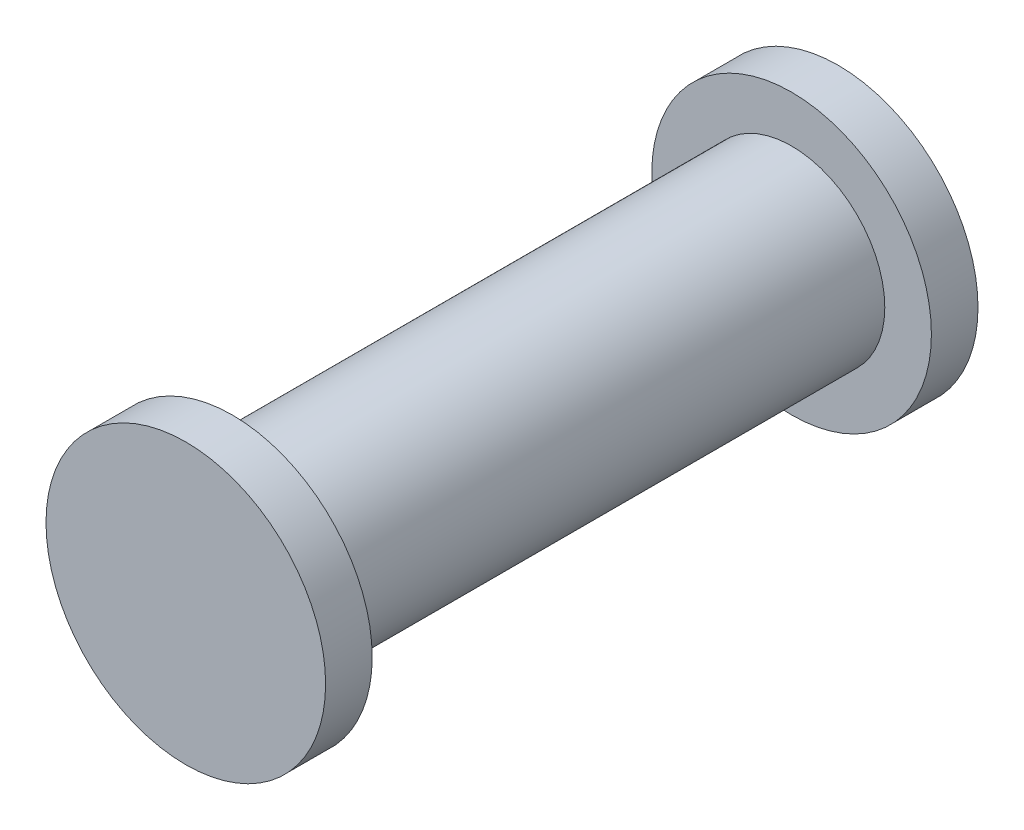
SolidWorks part; units mm, degrees
ref_plane "Front Plane" through (0, 0, 0) normal (0, 0, 1) x (1, 0, 0)
ref_plane "Top Plane" through (0, 0, 0) normal (0, 1, 0) x (1, 0, 0)
ref_plane "Right Plane" through (0, 0, 0) normal (1, 0, 0) x (0, 0, -1)
sketch "Sketch1" plane through (0, 0, 0) normal (0, 0, 1) x (1, 0, 0)
  circle A0 centre (0, 0) radius 10
  dimension "D1" = 20
extrude "Boss-Extrude1" add sketch "Sketch1" along normal blind 60
sketch "Sketch2" plane through (0, 0, 60) normal (0, 0, 1) x (1, 0, 0)
  circle A0 centre (0, 0) radius 15
  dimension "D1" = 30
extrude "Boss-Extrude2" add sketch "Sketch2" along normal blind 5
ref_plane "Plane1" through (0, 0, 30) normal (0, 0, -1) x (-1, 0, 0)
mirror "Mirror1" about plane through (0, 0, 30) normal (0, 0, -1) of "Boss-Extrude2"
